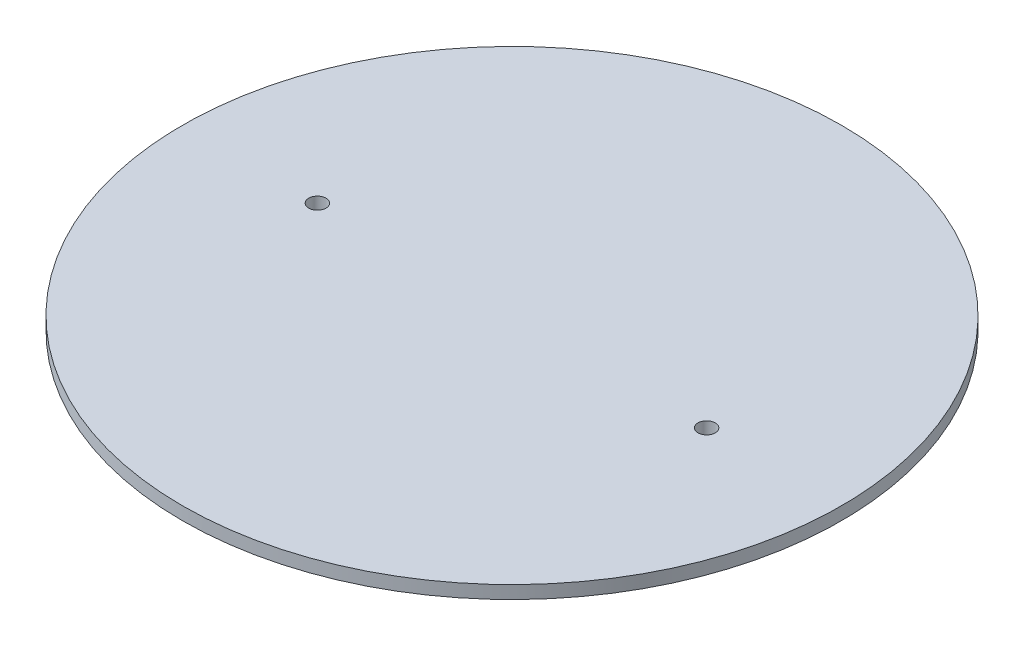
SolidWorks part; units mm, degrees
material "1060 Alloy"
ref_plane "Front Plane" through (0, 0, 0) normal (0, 0, 1) x (1, 0, 0)
ref_plane "Top Plane" through (0, 0, 0) normal (0, 1, 0) x (1, 0, 0)
ref_plane "Right Plane" through (0, 0, 0) normal (1, 0, 0) x (0, 0, -1)
sketch "Sketch1" plane through (0, 0, 0) normal (0, 1, 0) x (1, 0, 0)
  circle A0 centre (0, 0) radius 76.2
  dimension "D1" = 152.4
extrude "Boss-Extrude1" add sketch "Sketch1" along normal blind 3
sketch "Sketch2" plane through (0, 3, 0) normal (0, 1, 0) x (1, 0, 0)
  line L0 (-76.2, 0) -> (76.2, 0) construction
  circle A0 centre (-45, 0) radius 2
  circle A1 centre (45, 0) radius 2
  circle A2 centre (0, 0) radius 76.2 construction
  point P8 (76.2, 0)
  point P9 (0, 0)
  point P11 (0, 0)
  dimension "D1" = 4
  dimension "D2" = 4
  dimension "D3" = 90
  dimension "D4" = 45
extrude "Cut-Extrude1" cut sketch "Sketch2" against normal blind 10
